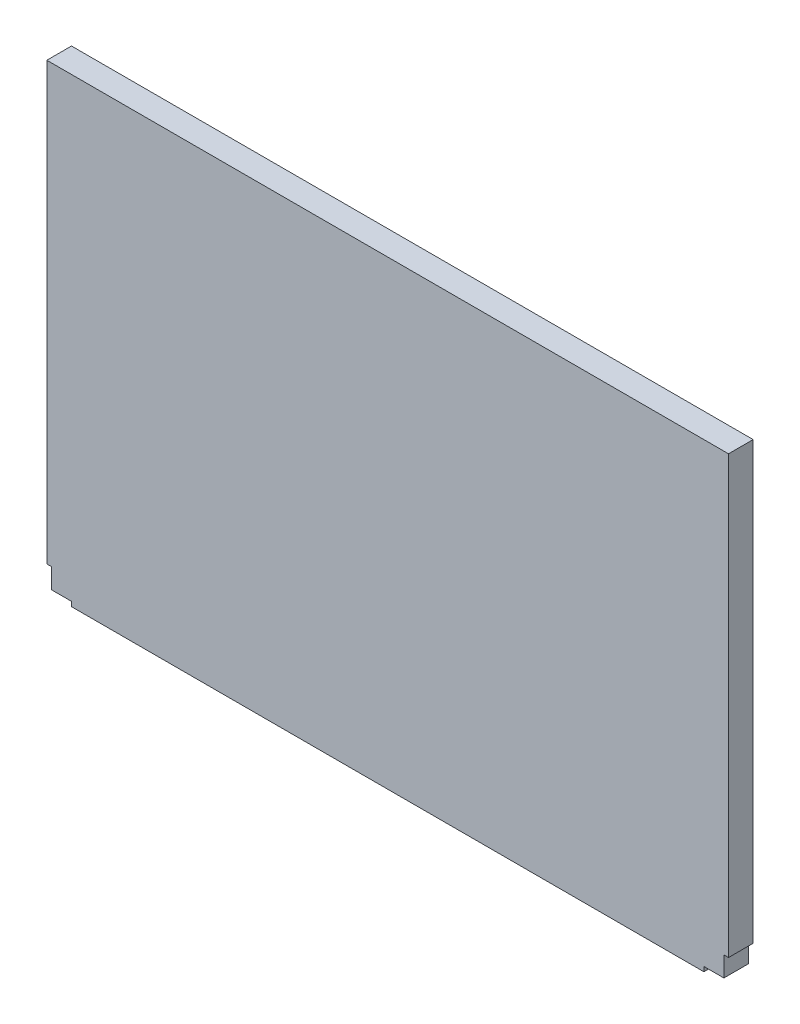
SolidWorks part; units mm, degrees
ref_plane "Alzado" through (0, 0, 0) normal (0, 0, 1) x (1, 0, 0)
ref_plane "Planta" through (0, 0, 0) normal (0, 1, 0) x (1, 0, 0)
ref_plane "Vista lateral" through (0, 0, 0) normal (1, 0, 0) x (0, 0, -1)
sketch "Croquis1" plane through (0, 0, 0) normal (0, 0, 1) x (1, 0, 0)
  line L1 (0, 0) -> (1405, 0)
  line L2 (0, 0) -> (0, -950)
  line L3 (0, -950) -> (1405, -950)
  line L4 (1405, 0) -> (1405, -950)
  dimension "D1" = 950
  dimension "D2" = 1405
extrude "Saliente-Extruir1" add sketch "Croquis1" along normal blind 50.8
sketch "Croquis2" plane through (0, 0, 50.8) normal (0, 0, 1) x (1, 0, 0)
  line L0 (0, -899.2) -> (9.525, -899.2)
  line L1 (0, 0) -> (0, -950) construction
  line L2 (9.525, -899.2) -> (9.525, -940.475)
  line L3 (9.525, -940.475) -> (50.8, -940.475)
  line L4 (50.8, -940.475) -> (50.8, -950)
  line L5 (0, -950) -> (1405, -950) construction
  line L6 (50.8, -950) -> (0, -950)
  line L7 (0, -950) -> (0, -899.2)
  line L8 (702.5, -950) -> (702.5, -975.043) construction
  line L9 (1405, -950) -> (1405, -899.2)
  line L10 (1354.2, -950) -> (1405, -950)
  line L11 (1354.2, -940.475) -> (1354.2, -950)
  line L12 (1395.475, -940.475) -> (1354.2, -940.475)
  line L13 (1395.475, -899.2) -> (1395.475, -940.475)
  line L14 (1405, -899.2) -> (1395.475, -899.2)
  dimension "D1" = 50.8
  dimension "D2" = 50.8
  dimension "D3" = 9.525
  dimension "D4" = 9.525
extrude "Cortar-Extruir1" cut sketch "Croquis2" against normal blind 51
